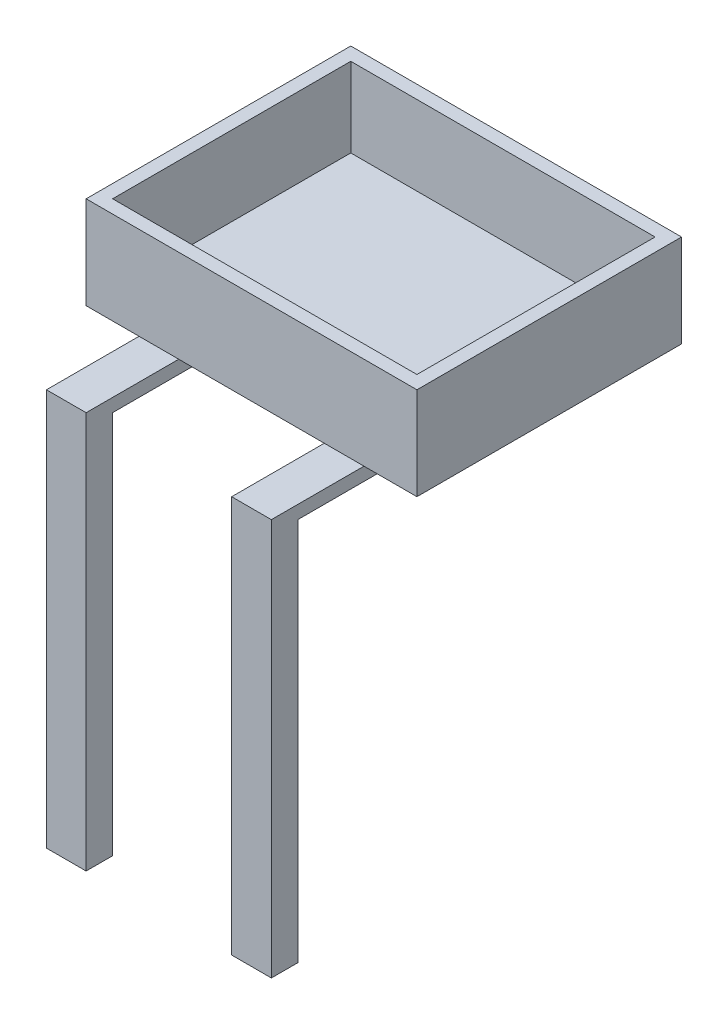
SolidWorks part; units mm, degrees
material "1.4003 (X2CrNi12)"
ref_plane "Alzado" through (0, 0, 0) normal (0, 0, 1) x (1, 0, 0)
ref_plane "Planta" through (0, 0, 0) normal (0, 1, 0) x (1, 0, 0)
ref_plane "Vista lateral" through (0, 0, 0) normal (1, 0, 0) x (0, 0, -1)
sketch "Croquis1" plane through (0, 0, 0) normal (0, 1, 0) x (1, 0, 0)
  line L1 (-125, 100) -> (125, 100)
  line L2 (-125, 100) -> (-125, -100)
  line L3 (-125, -100) -> (125, -100)
  line L4 (125, 100) -> (125, -100)
  line L5 (-125, 100) -> (125, -100) construction
  line L6 (-125, -100) -> (125, 100) construction
  point P0 (0, 0)
  dimension "D1" = 250
  dimension "D2" = 200
extrude "Saliente-Extruir1" add sketch "Croquis1" along normal blind 10
sketch "Croquis2" plane through (0, 10, 0) normal (0, 1, 0) x (1, 0, 0)
  line L1 (-125, 100) -> (125, 100)
  line L2 (-125, 100) -> (-125, -100)
  line L3 (-125, -100) -> (125, -100)
  line L4 (125, 100) -> (125, -100)
  line L7 (-115, 90) -> (115, 90)
  line L8 (-115, 90) -> (-115, -90)
  line L9 (-115, -90) -> (115, -90)
  line L10 (115, 90) -> (115, -90)
  point P0 (0, 0)
  point P7 (0, 0)
  dimension "D1" = 10
  dimension "D2" = 10
  dimension "D3" = 10
  dimension "D4" = 10
extrude "Saliente-Extruir2" add sketch "Croquis2" along normal blind 60
sketch "Croquis3" plane through (0, 0, 0) normal (0, -1, 0) x (1, 0, 0)
  line L0 (125, -100) -> (-125, -100) construction
  line L1 (-85, -100) -> (-55, -100)
  line L2 (-85, -100) -> (-85, 170)
  line L3 (-85, 170) -> (-55, 170)
  line L4 (-55, -100) -> (-55, 170)
  line L5 (-125, -100) -> (-125, 100) construction
  line L6 (55, -100) -> (85, -100)
  line L7 (55, -100) -> (55, 170)
  line L8 (55, 170) -> (85, 170)
  line L9 (85, -100) -> (85, 170)
  line L10 (125, 100) -> (125, -100) construction
  dimension "D1" = 30
  dimension "D2" = 30
  dimension "D3" = 40
  dimension "D4" = 40
  dimension "D5" = 270
  dimension "D6" = 270
extrude "Saliente-Extruir3" add sketch "Croquis3" along normal blind 10
sketch "Croquis4" plane through (0, -10, 0) normal (0, -1, 0) x (1, 0, 0)
  line L0 (-55, -100) -> (-55, 170) construction
  line L1 (-85, 170) -> (-55, 170)
  line L2 (-85, 170) -> (-85, 150)
  line L3 (-85, 150) -> (-55, 150)
  line L4 (-55, 170) -> (-55, 150)
  line L5 (85, -100) -> (85, 170) construction
  line L6 (55, 170) -> (85, 170)
  line L7 (55, 170) -> (55, 150)
  line L8 (55, 150) -> (85, 150)
  line L9 (85, 170) -> (85, 150)
  dimension "D1" = 20
  dimension "D2" = 20
extrude "Saliente-Extruir4" add sketch "Croquis4" along normal blind 290
